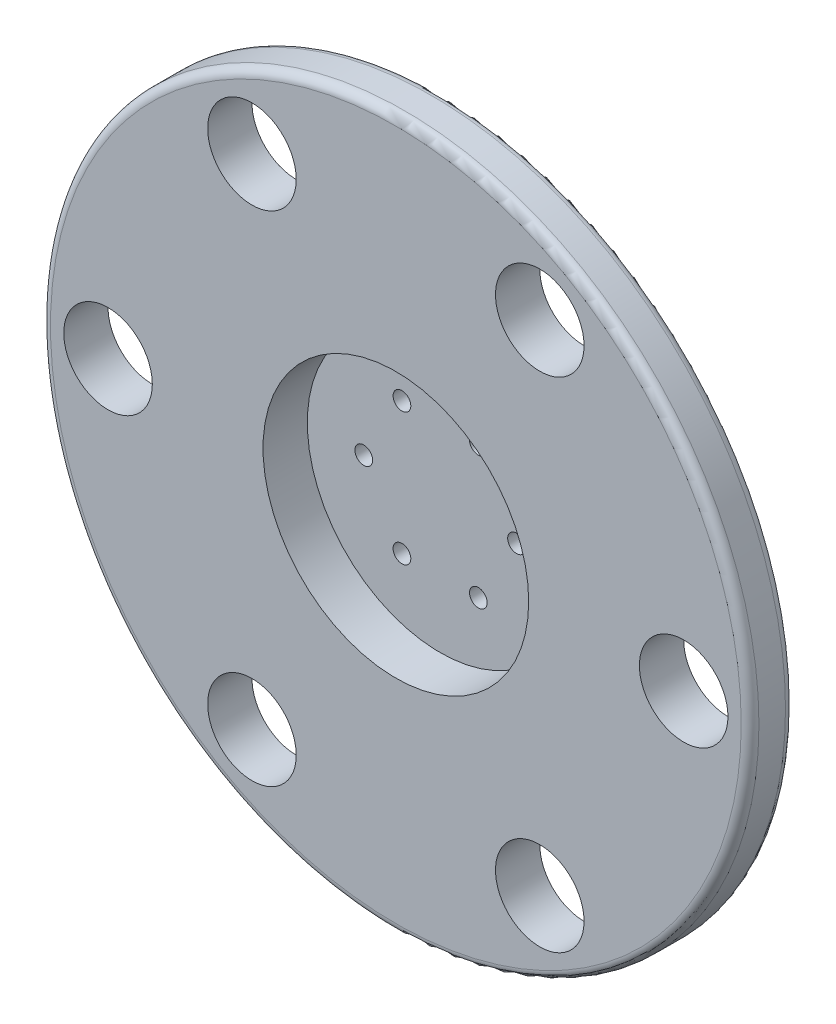
SolidWorks part; units mm, degrees
ref_plane "前视基准面" through (0, 0, 0) normal (0, 0, 1) x (1, 0, 0)
ref_plane "上视基准面" through (0, 0, 0) normal (0, 1, 0) x (1, 0, 0)
ref_plane "右视基准面" through (0, 0, 0) normal (1, 0, 0) x (0, 0, -1)
sketch "草图2" plane through (0, 0, 0) normal (0, 0, 1) x (1, 0, 0)
  circle A0 centre (0, 0) radius 80
  dimension "D1" = 160
extrude "凸台-拉伸1" add sketch "草图2" along normal blind 10
sketch "草图3" plane through (0, 0, 0) normal (0, 0, 1) x (1, 0, 0)
  circle A0 centre (0, 0) radius 32.5
  circle A1 centre (0, 0) radius 29.5 construction
  circle A2 centre (0, 0) radius 17.25 construction
  circle A3 centre (-17.25, 0) radius 2
  circle A4 centre (-8.625, 14.9389) radius 2
  circle A5 centre (8.625, 14.9389) radius 2
  circle A6 centre (17.25, 0) radius 2
  circle A7 centre (8.625, -14.9389) radius 2
  circle A8 centre (-8.625, -14.9389) radius 2
  point P20 (0, 0)
  dimension "D1" = 65
  dimension "D2" = 59
  dimension "D3" = 59
  dimension "D4" = 34.5
  dimension "D5" = 4
  dimension "D6" = 6
extrude "凸台-拉伸2" add sketch "草图3" against normal blind 10 contours A0
sketch "草图4" plane through (0, 0, 0) normal (0, 0, 1) x (1, 0, 0)
  line L0 (0, 0) -> (-29.5, 0)
  circle A0 centre (0, 0) radius 32.5
  circle A1 centre (0, 0) radius 29.5 construction
  circle A2 centre (0, 0) radius 17.25 construction
  circle A3 centre (-17.25, 0) radius 2
  circle A4 centre (-8.625, 14.9389) radius 2
  circle A5 centre (8.625, 14.9389) radius 2
  circle A6 centre (17.25, 0) radius 2
  circle A7 centre (8.625, -14.9389) radius 2
  circle A8 centre (-8.625, -14.9389) radius 2
  point P21 (0, 0)
  dimension "D1" = 65
  dimension "D2" = 59
  dimension "D3" = 34.5
  dimension "D4" = 4
  dimension "D5" = 6
extrude "切除-拉伸1" cut sketch "草图4" against normal blind 10 contours A4 | A5 | A6 | A7 | A8 | A3
sketch "草图5" plane through (0, 0, 0) normal (0, 0, 1) x (1, 0, 0)
  circle A0 centre (0, 0) radius 30
  dimension "D1" = 60
extrude "切除-拉伸2" cut sketch "草图5" along normal blind 10
sketch "草图6" plane through (0, 0, 0) normal (0, 0, 1) x (1, 0, 0)
  line L0 (0, 0) -> (-80, 0)
  circle A0 centre (0, 0) radius 80 construction
  circle A1 centre (0, 0) radius 48.25 construction
  circle A2 centre (-65, 0) radius 10
  circle A3 centre (-32.5, 56.2917) radius 10
  circle A4 centre (32.5, 56.2917) radius 10
  circle A5 centre (65, 0) radius 10
  circle A6 centre (32.5, -56.2917) radius 10
  circle A7 centre (-32.5, -56.2917) radius 10
  point P22 (0, 0)
  dimension "D1" = 96.5
  dimension "D2" = 20
  dimension "D3" = 15
  dimension "D4" = 6
extrude "切除-拉伸3" cut sketch "草图6" along normal blind 10 contours A2 | A3 | A4 | A5 | A6 | A7
fillet "圆角1" radius 2 2 edges at (80, 0, 10) (80, 0, 0)
